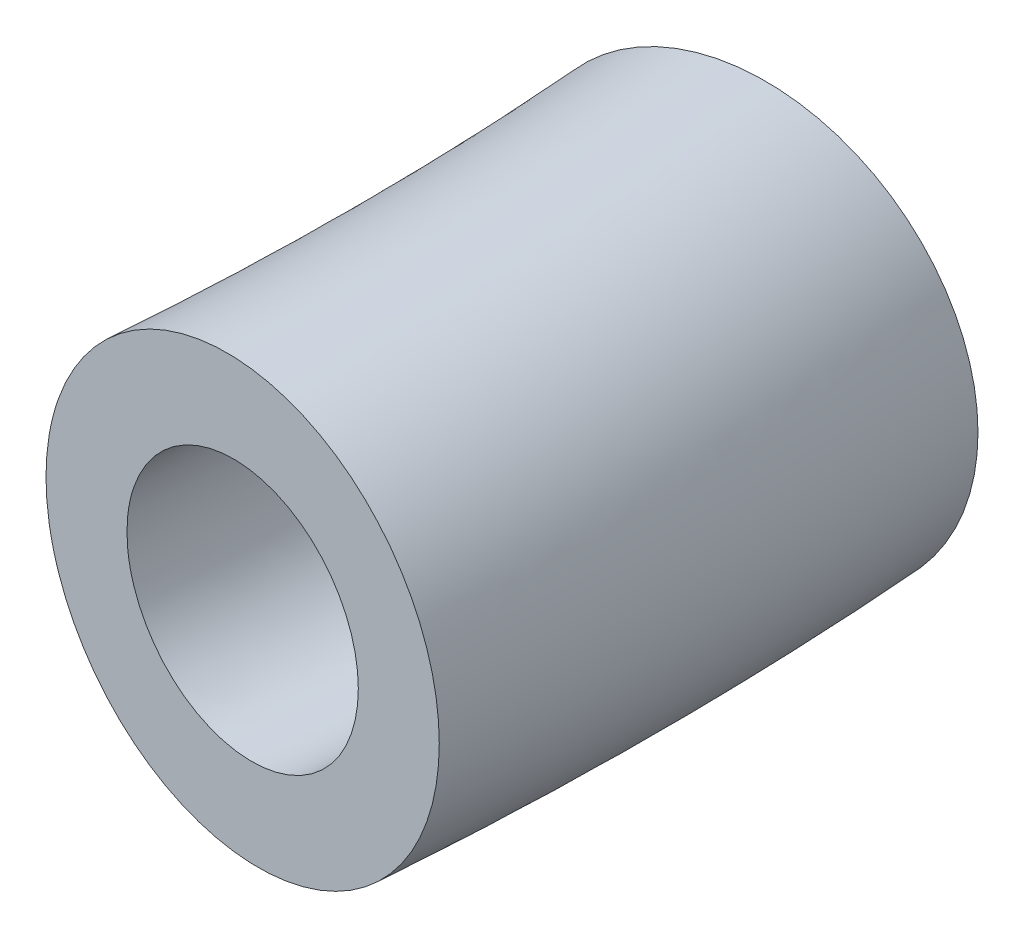
SolidWorks part; units mm, degrees
material "HT200"
ref_plane "前视基准面" through (0, 0, 0) normal (0, 0, 1) x (1, 0, 0)
ref_plane "上视基准面" through (0, 0, 0) normal (0, 1, 0) x (1, 0, 0)
ref_plane "右视基准面" through (0, 0, 0) normal (1, 0, 0) x (0, 0, -1)
sketch "草图1" plane through (0, 0, 0) normal (0, 0, 1) x (1, 0, 0)
  circle A0 centre (0, 0) radius 25
  circle A1 centre (0, 0) radius 42.5
  dimension "D1" = 50
  dimension "D2" = 85
sketch "草图2" plane through (0, 0, 0) normal (0, 1, 0) x (1, 0, 0)
  line L0 (0, 50) -> (0, -50) construction
  line L1 (-61.8881, 0) -> (79.7203, 0) construction
  line L2 (-2, 50) -> (-2, -50) construction
  spline S0 degree 2 poles (-2, 50) (2, 0) (-2, -50) knots 0 0 0 1 1 1
  dimension "D1" = 100
  dimension "D2" = 50
  dimension "D3" = 100
  dimension "D4" = 50
  dimension "D5" = 2
sweep "扫描1" add profiles "草图1" path "草图2"
